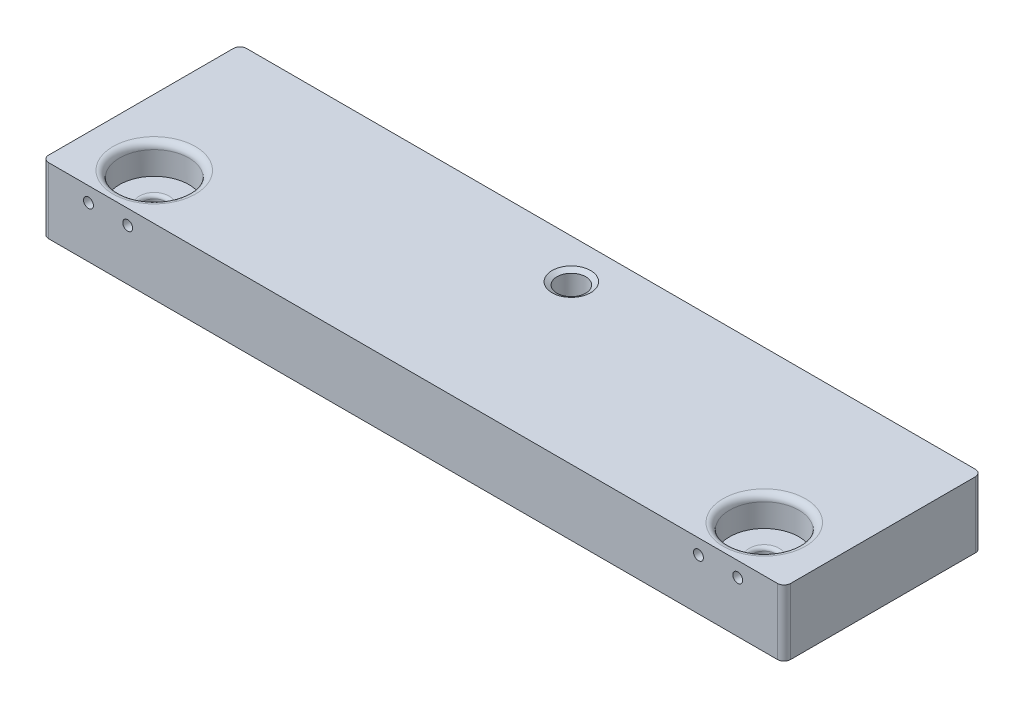
SolidWorks part; units mm, degrees
ref_plane "Front Plane" through (0, 0, 0) normal (0, 0, 1) x (1, 0, 0)
ref_plane "Top Plane" through (0, 0, 0) normal (0, 1, 0) x (1, 0, 0)
ref_plane "Right Plane" through (0, 0, 0) normal (1, 0, 0) x (0, 0, -1)
sketch "Sketch1" plane through (0, 0, 0) normal (0, 1, 0) x (1, 0, 0)
  line L0 (0, -55) -> (0, 55) construction
  line L1 (-112.5, -30) -> (112.5, -30)
  line L2 (-112.5, -30) -> (-112.5, 30)
  line L3 (-112.5, 30) -> (112.5, 30)
  line L4 (112.5, -30) -> (112.5, 30)
  line L5 (-112.5, -30) -> (112.5, 30) construction
  line L6 (-112.5, 30) -> (112.5, -30) construction
  circle A0 centre (92.5, -16) radius 3.5
  circle A1 centre (-92.5, -16) radius 3.5
  circle A2 centre (0, 18) radius 4.3498
  point P0 (0, 0)
  point P14 (0, 0)
  dimension "D5" = 7
  dimension "D6" = 8.6996
  dimension "D1" = 225
  dimension "D2" = 60
  dimension "D3" = 185
  dimension "D4" = 14
  dimension "D7" = 12
extrude "Boss-Extrude1" add sketch "Sketch1" along normal blind 20
sketch "Sketch2" plane through (0, 20, 0) normal (0, 1, 0) x (1, 0, 0)
  line L0 (0, -55) -> (0, 55) construction
  circle A0 centre (-92.5, -16) radius 10.5
  circle A1 centre (92.5, -16) radius 10.5
  dimension "D1" = 21
extrude "Cut-Extrude1" cut sketch "Sketch2" against normal blind 9
sketch "Sketch3" plane through (0, 0, 30) normal (0, 0, 1) x (1, 0, 0)
  line L0 (-82, 11) -> (-103, 11) construction
  line L1 (-82, 20) -> (-103, 20) construction
  line L2 (-82, 11) -> (-103, 11) construction
  line L3 (-82, 20) -> (-103, 20) construction
  line L4 (-82, 11) -> (-82, 20) construction
  line L5 (-103, 11) -> (-103, 20) construction
  line L6 (-92.5, 20) -> (-92.5, 11) construction
  line L7 (0, -55) -> (0, 55) construction
  circle A0 centre (-98.45, 15.5) radius 1.5
  circle A2 centre (-86.55, 15.5) radius 1.5
  circle A3 centre (98.45, 15.5) radius 1.5
  circle A4 centre (86.55, 15.5) radius 1.5
  point P10 (-82, 15.5)
  dimension "D1" = 3
  dimension "D2" = 11.9
extrude "Cut-Extrude2" cut sketch "Sketch3" against normal up to next
fillet "Fillet1" radius 2 6 edges at (-112.5, 10, 30) (-112.5, 10, -30) (-92.5, 20, 26.5) (92.5, 20, 5.5) (112.5, 10, -30) (112.5, 10, 30)
fillet "Fillet2" radius 1 4 edges at (92.5, 0, 19.5) (92.5, 11, 12.5) (-92.5, 11, 19.5) (-92.5, 0, 12.5)
chamfer "Chamfer1" distance 1.5 angle 30 2 edges at (0, 0, -13.6502) (0, 20, -13.6502)
